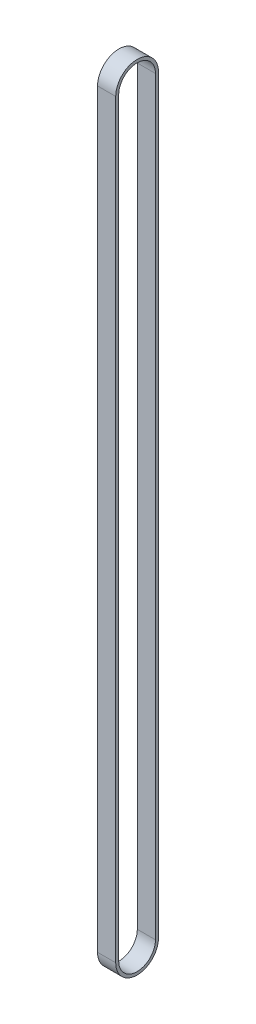
SolidWorks part; units mm, degrees
material "6063-T5"
ref_plane "Front Plane" through (0, 0, 0) normal (1, 0, 0) x (0, 1, 0)
ref_plane "Top Plane" through (0, 0, 0) normal (0, 0, 1) x (0, 1, 0)
ref_plane "Right Plane" through (0, 0, 0) normal (0, 1, 0) x (-1, 0, 0)
sketch "Sketch1" plane through (0, 0, 0) normal (1, 0, 0) x (0, 1, 0)
  line L0 (-125, 0) -> (125, 0) construction
  line L1 (-125, 6.125) -> (125, 6.125)
  line L2 (-125, -6.125) -> (125, -6.125)
  line L3 (-125, 7.125) -> (125, 7.125)
  line L4 (-125, -7.125) -> (125, -7.125)
  arc A0 (-125, 6.125) -> (-125, -6.125) centre (-125, 0) ccw
  arc A1 (125, -6.125) -> (125, 6.125) centre (125, 0) ccw
  arc A2 (125, -7.125) -> (125, 7.125) centre (125, 0) ccw
  arc A3 (-125, 7.125) -> (-125, -7.125) centre (-125, 0) ccw
  point P2 (0, 0)
  dimension "D2" = 6.125
  dimension "D1" = 250
  dimension "D3" = 1
extrude "Boss-Extrude1" add sketch "Sketch1" along normal blind 6.05
